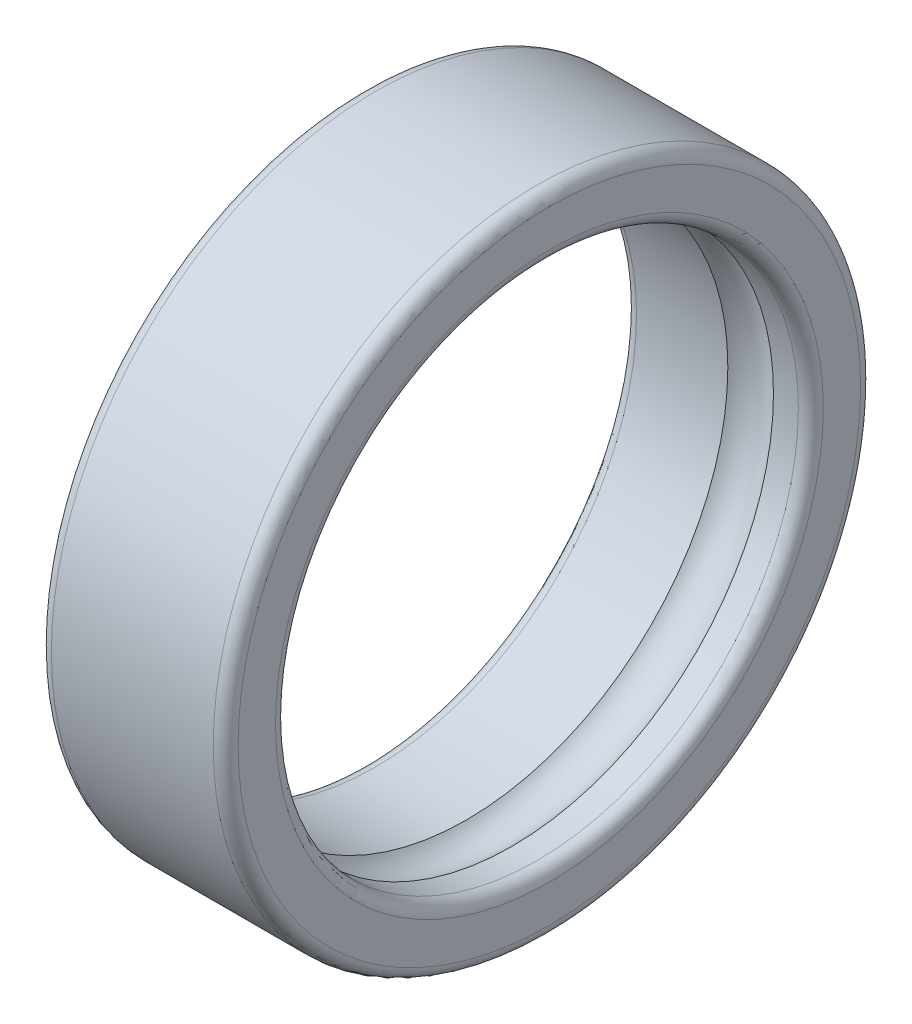
SolidWorks part; units mm, degrees
ref_plane "Front Plane" through (0, 0, 0) normal (0, 0, 1) x (1, 0, 0)
ref_plane "Top Plane" through (0, 0, 0) normal (0, 1, 0) x (1, 0, 0)
ref_plane "Right Plane" through (0, 0, 0) normal (1, 0, 0) x (0, 0, -1)
sketch "Sketch1" plane through (0, 0, 0) normal (0, 0, 1) x (1, 0, 0)
  line L0 (-7.5, 22) -> (-7.5, 25)
  line L1 (-6.5, 26) -> (6.5, 26)
  line L2 (7.5, 25) -> (7.5, 22)
  line L3 (6.5, 21) -> (4.5, 21)
  line L4 (0.8339, 21) -> (-6.5, 21)
  line L5 (16.0583, 0) -> (33.1265, 0) construction
  arc A0 (-7.5, 22) -> (-6.5, 21) centre (-6.5, 22) ccw
  arc A1 (4.5, 21) -> (0.8339, 21) centre (2.667, 19.3) ccw
  arc A2 (6.5, 21) -> (7.5, 22) centre (6.5, 22) ccw
  arc A3 (7.5, 25) -> (6.5, 26) centre (6.5, 25) ccw
  arc A4 (-6.5, 26) -> (-7.5, 25) centre (-6.5, 25) ccw
  point P7 (0, 26)
  point P11 (-7.5, 21)
  point P14 (7.5, 21)
  point P17 (7.5, 26)
  point P20 (-7.5, 26)
  dimension "D3" = 2.5
  dimension "D7" = 1
  dimension "D6" = 19.3
  dimension "D1" = 26
  dimension "D2" = 15
  dimension "D4" = 5
  dimension "D5" = 2
revolve "Revolve1" add sketch "Sketch1" angle 360 about L5
